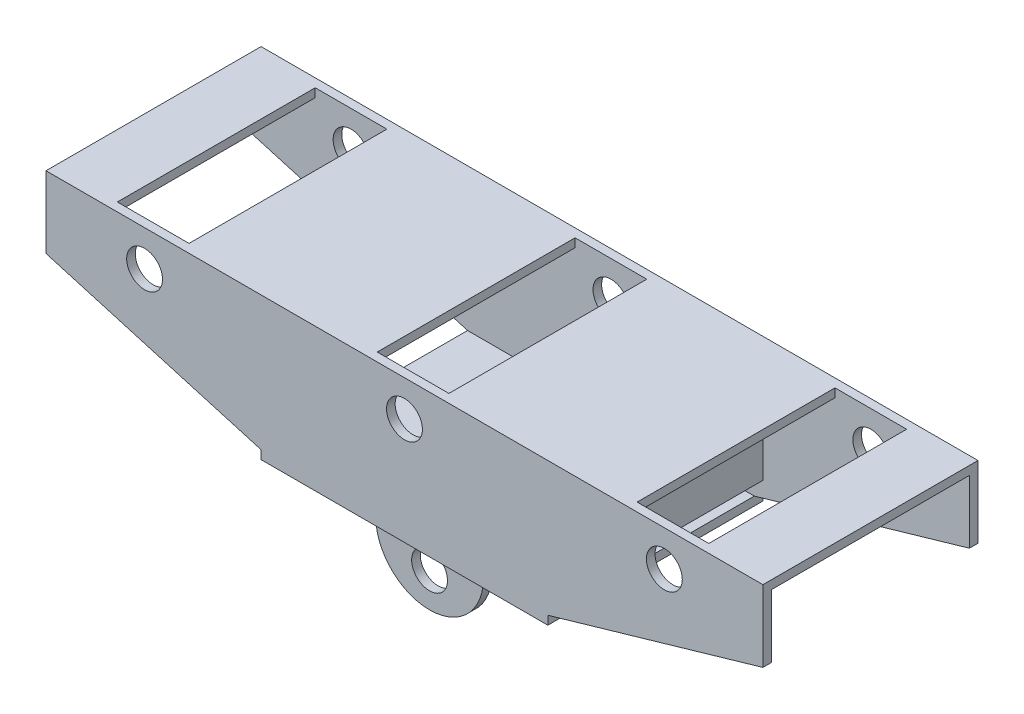
SolidWorks part; units mm, degrees
ref_plane "前视基准面" through (0, 0, 0) normal (0, 0, 1) x (1, 0, 0)
ref_plane "上视基准面" through (0, 0, 0) normal (0, 1, 0) x (1, 0, 0)
ref_plane "右视基准面" through (0, 0, 0) normal (1, 0, 0) x (0, 0, -1)
sketch "草图1" plane through (0, 0, 0) normal (0, 0, 1) x (1, 0, 0)
  line L0 (0, -1000) -> (0, 49000) construction
  line L1 (-300, 0) -> (-200, 0)
  line L2 (-200, 0) -> (-200, -150)
  line L3 (-200, -150) -> (-212, -150)
  line L4 (-212, -150) -> (-212, -12)
  line L5 (-212, -12) -> (-300, -12)
  line L6 (-300, -12) -> (-300, 0)
  line L7 (300, 0) -> (200, 0)
  line L8 (200, 0) -> (200, -150)
  line L9 (200, -150) -> (212, -150)
  line L10 (212, -150) -> (212, -12)
  line L11 (212, -12) -> (300, -12)
  line L12 (300, -12) -> (300, 0)
  dimension "D1" = 12
  dimension "D2" = 12
  dimension "D3" = 100
  dimension "D4" = 150
  dimension "D5" = 200
extrude "凸台-拉伸1" add sketch "草图1" along normal blind 276
sketch "草图2" plane through (0, 0, 276) normal (0, 0, 1) x (1, 0, 0)
  line L0 (-500, 12) -> (500, 12)
  line L1 (0, -1000) -> (0, 49000) construction
  line L2 (-200, 0) -> (-300, 0) construction
  line L3 (500, 12) -> (500, -88)
  line L4 (500, -88) -> (200, -175)
  line L5 (200, -175) -> (-200, -175)
  line L6 (-200, -175) -> (-500, -88)
  line L7 (-500, -88) -> (-500, 12)
  line L9 (200, 0) -> (200, -150) construction
  line L10 (-212, -150) -> (-200, -150) construction
  dimension "D2" = 12
  dimension "D1" = 1000
  dimension "D3" = 25
  dimension "D5" = 100
extrude "凸台-拉伸2" add sketch "草图2" along normal blind 12
pattern_linear "阵列(线性)1" count 2 spacing 288 along (0, 0, -1) of "凸台-拉伸2"
sketch "草图3" plane through (500, 0, 0) normal (1, 0, 0) x (0, 0, -1)
  line L1 (-276, 0) -> (0, 0)
  line L2 (-276, 0) -> (-276, 12)
  line L3 (-276, 12) -> (0, 12)
  line L4 (0, 0) -> (0, 12)
extrude "凸台-拉伸3" add sketch "草图3" against normal blind 1000
sketch "草图4" plane through (0, -175, 0) normal (0, -1, 0) x (1, 0, 0)
  line L1 (-200, 288) -> (200, 288)
  line L2 (-200, 288) -> (-200, -12)
  line L3 (-200, -12) -> (200, -12)
  line L4 (200, 288) -> (200, -12)
extrude "凸台-拉伸4" add sketch "草图4" along normal blind 12
sketch "草图5" plane through (0, -187, 0) normal (0, -1, 0) x (-1, 0, 0)
  line L1 (200, -138) -> (-49800, -138) construction
  line L2 (200, -288) -> (200, 12) construction
  line L3 (-200, 12) -> (-200, -288) construction
  line L4 (0, -1000) -> (0, 49000) construction
  line L6 (75, -253) -> (-75, -253)
  line L7 (75, -253) -> (75, -241)
  line L8 (75, -241) -> (-75, -241)
  line L9 (-75, -253) -> (-75, -241)
  line L10 (75, -35) -> (-75, -35)
  line L11 (75, -35) -> (75, -23)
  line L12 (75, -23) -> (-75, -23)
  line L13 (-75, -35) -> (-75, -23)
  point P4 (200, -138)
  point P7 (-200, -138)
  dimension "D1" = 12
  dimension "D2" = 12
  dimension "D3" = 230
  dimension "D4" = 150
extrude "凸台-拉伸5" add sketch "草图5" along normal blind 100
sketch "草图6" plane through (0, 0, 253) normal (0, 0, 1) x (1, 0, 0)
  line L0 (0, -1000) -> (0, 49000) construction
  line L1 (500, 12) -> (-500, 12) construction
  line L9 (75, -287) -> (75, -187) construction
  line L11 (-75, -287) -> (-75, -187) construction
  line L13 (-922.5242, -286) -> (49077.4758, -286) construction
  line L14 (75, -287) -> (-75, -287) construction
  line L15 (75, -211) -> (75, -287)
  line L16 (75, -287) -> (-75, -287)
  line L17 (-75, -287) -> (-75, -211)
  circle A0 centre (0, -238) radius 25
  arc A1 (75, -211) -> (-75, -211) centre (0, -211) cw
  dimension "D1" = 50
  dimension "D3" = 1
  dimension "D2" = 250
extrude "切除-拉伸1" cut sketch "草图6" against normal through all
sketch "草图7" plane through (0, 0, 288) normal (0, 0, 1) x (1, 0, 0)
  line L0 (-969.9743, -38) -> (49030.0257, -38) construction
  line L1 (500, 12) -> (-500, 12) construction
  line L2 (0, -1000) -> (0, 49000) construction
  circle A0 centre (-362.5, -38) radius 25
  circle A1 centre (362.5, -38) radius 25
  circle A2 centre (0, -38) radius 25
  dimension "D2" = 50
  dimension "D1" = 50
  dimension "D3" = 725
extrude "切除-拉伸2" cut sketch "草图7" against normal through all
sketch "草图8" plane through (0, 0, 0) normal (0, -1, 0) x (1, 0, 0)
  line L0 (0, -1000) -> (0, 49000) construction
  line L1 (200, 276) -> (500, 276) construction
  line L2 (312.5, 276) -> (412.5, 276)
  line L3 (312.5, 276) -> (312.5, 0)
  line L4 (312.5, 0) -> (412.5, 0)
  line L5 (412.5, 276) -> (412.5, 0)
  line L6 (200, 0) -> (500, 0) construction
  line L7 (-500, 276) -> (-300, 276) construction
  line L8 (-412.5, 276) -> (-312.5, 276)
  line L9 (-412.5, 276) -> (-412.5, 0)
  line L10 (-412.5, 0) -> (-312.5, 0)
  line L11 (-312.5, 276) -> (-312.5, 0)
  line L12 (-500, 0) -> (-200, 0) construction
  line L13 (-362.5, -800.4883) -> (-362.5, 49199.5117) construction
  line L14 (-50, 276) -> (50, 276)
  line L15 (-50, 276) -> (-50, 0)
  line L16 (-50, 0) -> (50, 0)
  line L17 (50, 276) -> (50, 0)
  line L18 (362.5, -833.0843) -> (362.5, 49166.9157) construction
  dimension "D1" = 100
  dimension "D2" = 725
extrude "切除-拉伸3" cut sketch "草图8" against normal through all
